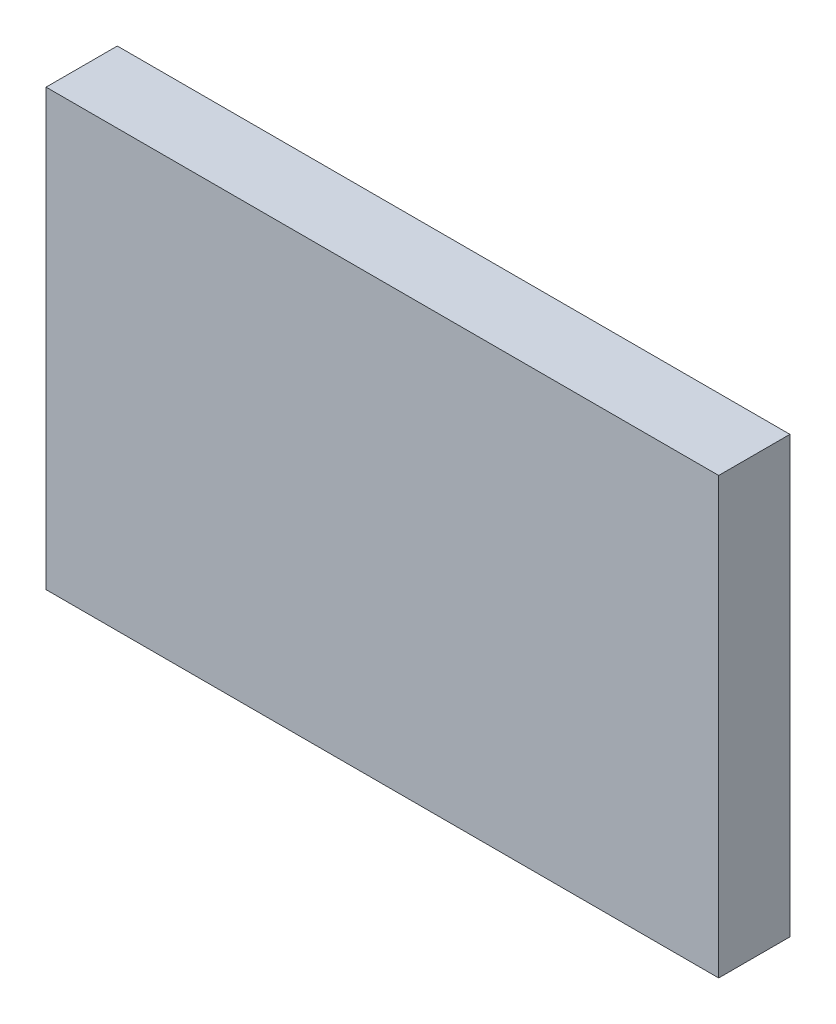
SolidWorks part; units mm, degrees
ref_plane "Plan de face" through (0, 0, 0) normal (0, 0, 1) x (1, 0, 0)
ref_plane "Plan de dessus" through (0, 0, 0) normal (0, 1, 0) x (1, 0, 0)
ref_plane "Plan de droite" through (0, 0, 0) normal (1, 0, 0) x (0, 0, -1)
sketch "Esquisse1" plane through (0, 0, 0) normal (0, 0, 1) x (1, 0, 0)
  line L1 (42.5, -27.5) -> (-42.5, -27.5)
  line L2 (42.5, -27.5) -> (42.5, 27.5)
  line L3 (42.5, 27.5) -> (-42.5, 27.5)
  line L4 (-42.5, -27.5) -> (-42.5, 27.5)
  line L5 (42.5, -27.5) -> (-42.5, 27.5) construction
  line L6 (42.5, 27.5) -> (-42.5, -27.5) construction
  point P0 (0, 0)
  dimension "D1" = 85
  dimension "D2" = 55
extrude "Boss.-Extru.1" add sketch "Esquisse1" along normal blind 9
